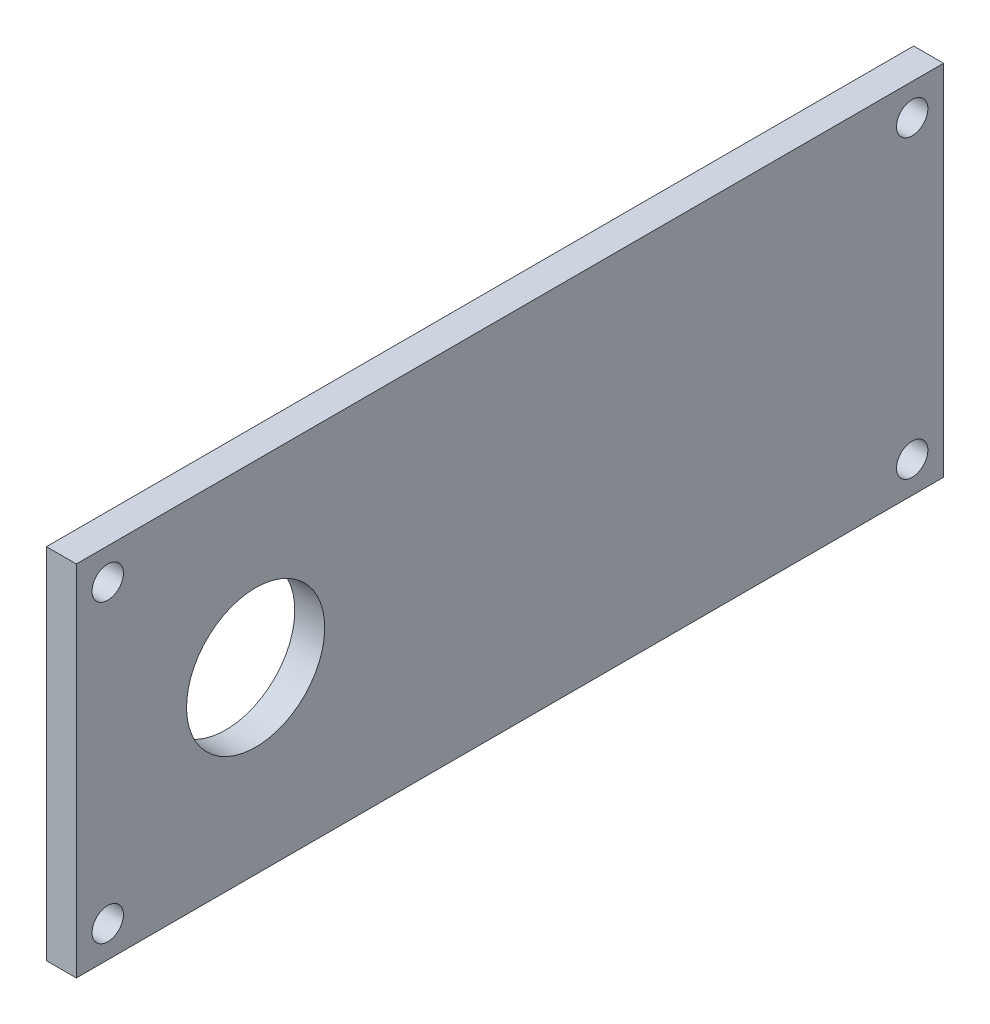
SolidWorks part; units mm, degrees
ref_plane "Front Plane" through (0, 0, 0) normal (0, 0, 1) x (1, 0, 0)
ref_plane "Top Plane" through (0, 0, 0) normal (0, 1, 0) x (1, 0, 0)
ref_plane "Right Plane" through (0, 0, 0) normal (1, 0, 0) x (0, 0, -1)
sketch "Sketch1" plane through (-82.9702, 0, 0) normal (-1, 0, 0) x (0, 0, 1)
  line L1 (-158.258, -79.6078) -> (-20.158, -79.6078) construction
  line L2 (-20.158, -79.6078) -> (-20.158, -22.5078) construction
  line L3 (-20.158, -22.5078) -> (-158.258, -22.5078) construction
  line L4 (-158.258, -22.5078) -> (-158.258, -79.6078) construction
  line L6 (-158.258, -79.6078) -> (-20.158, -79.6078)
  line L7 (-20.158, -79.6078) -> (-20.158, -22.5078)
  line L8 (-20.158, -22.5078) -> (-158.258, -22.5078)
  line L9 (-158.258, -22.5078) -> (-158.258, -79.6078)
  circle A0 centre (-153.258, -27.5078) radius 2.5 construction
  circle A1 centre (-153.258, -74.6078) radius 2.5 construction
  circle A8 centre (-25.158, -27.5078) radius 2.5 construction
  circle A9 centre (-25.158, -74.6078) radius 2.5 construction
  circle A12 centre (-153.258, -27.5078) radius 2.5
  circle A14 centre (-153.258, -74.6078) radius 2.5
  circle A17 centre (-25.158, -27.5078) radius 2.5
  circle A18 centre (-25.158, -74.6078) radius 2.5
  circle A21 centre (-48.708, -51.0578) radius 11 construction
  circle A22 centre (-48.708, -51.0578) radius 11
extrude "Boss-Extrude1" add sketch "Sketch1" along normal blind 4.7625
